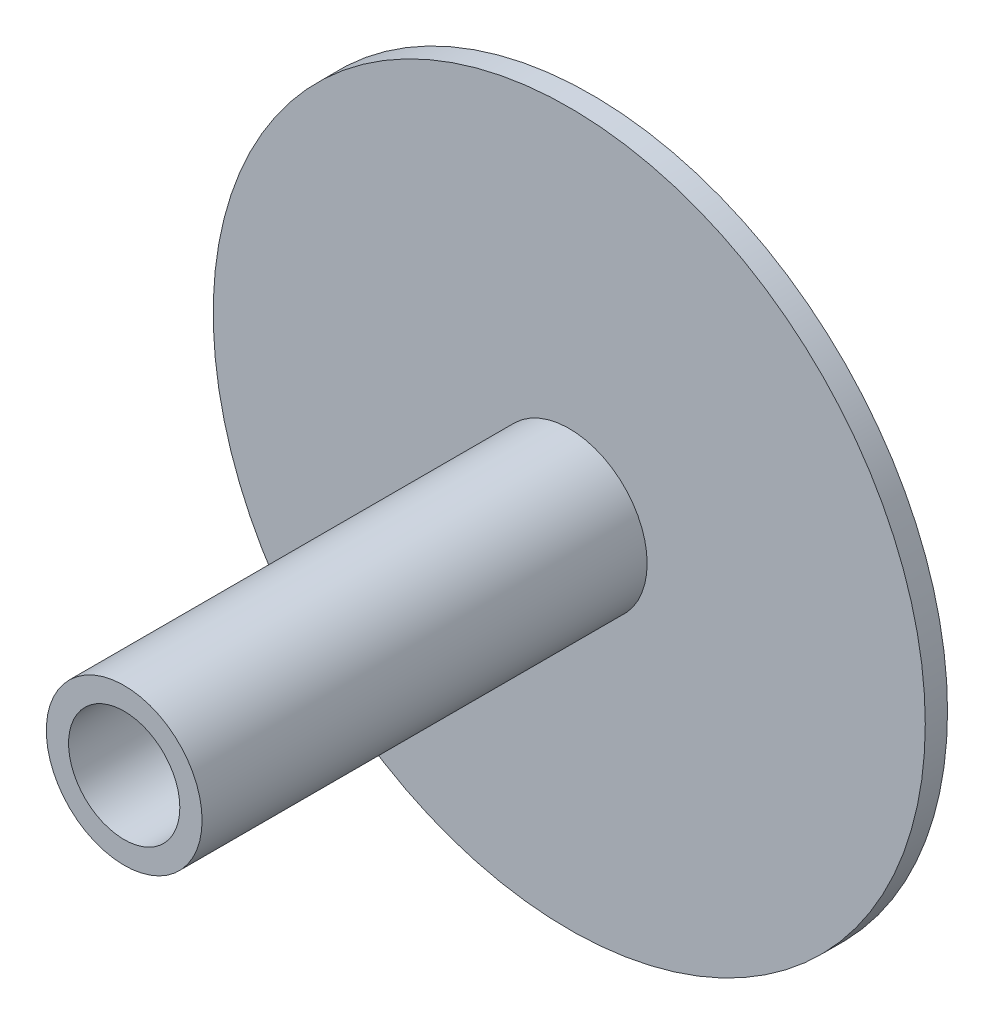
SolidWorks part; units mm, degrees
ref_plane "Front" through (0, 0, 0) normal (0, 0, 1) x (1, 0, 0)
ref_plane "Top" through (0, 0, 0) normal (0, 1, 0) x (1, 0, 0)
ref_plane "Right" through (0, 0, 0) normal (1, 0, 0) x (0, 0, -1)
sketch "Sketch1" plane through (0, 0, 0) normal (0, 0, 1) x (1, 0, 0)
  circle A0 centre (0, 0) radius 15 construction
  circle A1 centre (0, 0) radius 16
  dimension "D1" = 30
  dimension "D2" = 1
extrude "Boss-Extrude1" add sketch "Sketch1" along normal blind 1 contours A1
sketch "Sketch2" plane through (0, 0, 1) normal (0, 0, 1) x (1, 0, 0)
  circle A0 centre (0, 0) radius 2.5 construction
  circle A1 centre (0, 0) radius 3.5
  dimension "D2" = 1
  dimension "D1" = 5
extrude "Boss-Extrude2" add sketch "Sketch2" along normal blind 20
sketch "Sketch3" plane through (0, 0, 21) normal (0, 0, 1) x (1, 0, 0)
  circle A0 centre (0, 0) radius 2.5
  dimension "D1" = 5
extrude "Cut-Extrude1" cut sketch "Sketch3" against normal through all both and the other way through all contours A0
equation "\"D1@Sketch1\"=\"Cavity_Diameter\""
equation "\"Wall_Thickness\"= 1"
equation "\"Cavity_Diameter\"=30"
equation "\"D2@Sketch1\"=\"Wall_Thickness\""
equation "\"D1@Boss-Extrude1\"=\"Wall_Thickness\""
equation "\"Outlet_Diameter\" = 5"
equation "\"D1@Sketch2\"=\"Outlet_Diameter\""
equation "\"Outlet_Length\"= 20"
equation "\"D1@Boss-Extrude2\"=\"Outlet_Length\""
equation "\"D1@Sketch3\"=\"Outlet_Diameter\""
